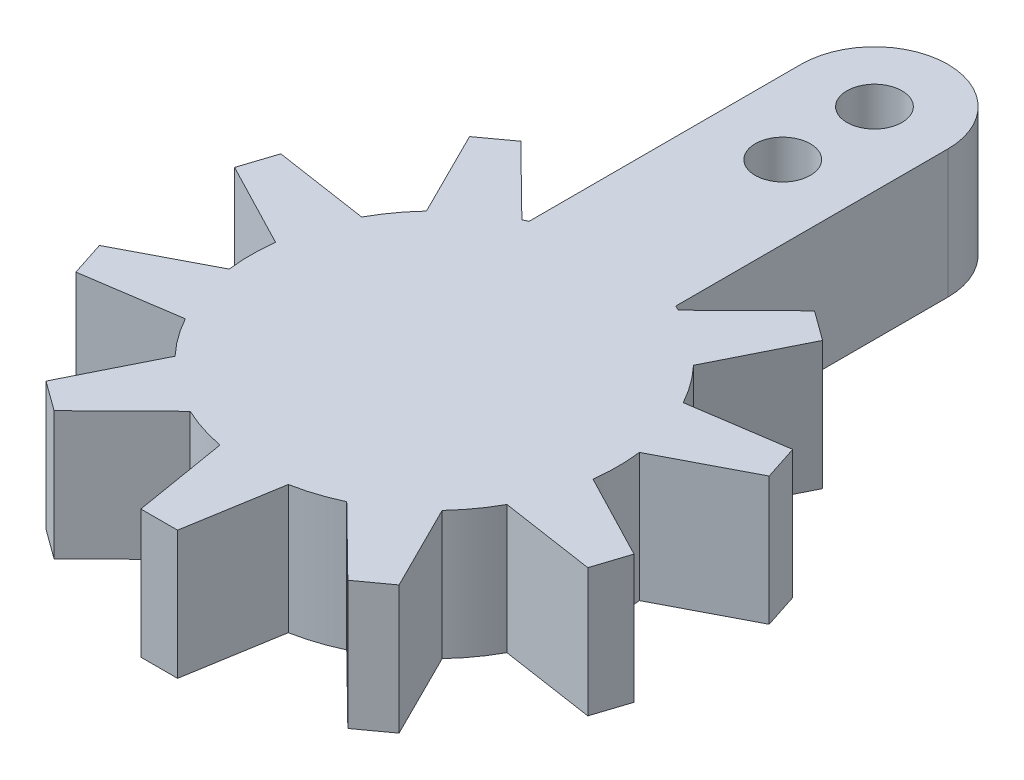
SolidWorks part; units mm, degrees
ref_plane "Front Plane" through (0, 0, 0) normal (0, 0, 1) x (1, 0, 0)
ref_plane "Top Plane" through (0, 0, 0) normal (0, 1, 0) x (1, 0, 0)
ref_plane "Right Plane" through (0, 0, 0) normal (1, 0, 0) x (0, 0, -1)
sketch "Sketch1" plane through (0, 0, 0) normal (0, 1, 0) x (1, 0, 0)
  line L0 (0, 15) -> (0, 10) construction
  line L1 (-1, 15) -> (1, 15)
  line L2 (-1, 15) -> (-2, 9)
  line L3 (1, 15) -> (2, 9)
  line L4 (-2, 9) -> (2, 9)
  line L5 (3.672, 8.4567) -> (6.9081, 6.1056)
  line L6 (9.6258, 11.5475) -> (6.9081, 6.1056)
  line L7 (8.0078, 12.723) -> (9.6258, 11.5475)
  line L8 (8.0078, 12.723) -> (3.672, 8.4567)
  line L9 (7.9415, 4.6833) -> (9.1775, 0.879)
  line L10 (14.5749, 3.6842) -> (9.1775, 0.879)
  line L11 (13.9568, 5.5863) -> (14.5749, 3.6842)
  line L12 (13.9568, 5.5863) -> (7.9415, 4.6833)
  line L13 (9.1775, -0.879) -> (7.9415, -4.6833)
  line L14 (13.9568, -5.5863) -> (7.9415, -4.6833)
  line L15 (14.5749, -3.6842) -> (13.9568, -5.5863)
  line L16 (14.5749, -3.6842) -> (9.1775, -0.879)
  line L17 (6.9081, -6.1056) -> (3.672, -8.4567)
  line L18 (8.0078, -12.723) -> (3.672, -8.4567)
  line L19 (9.6258, -11.5475) -> (8.0078, -12.723)
  line L20 (9.6258, -11.5475) -> (6.9081, -6.1056)
  line L21 (2, -9) -> (-2, -9)
  line L22 (-1, -15) -> (-2, -9)
  line L23 (1, -15) -> (-1, -15)
  line L24 (1, -15) -> (2, -9)
  line L25 (-3.672, -8.4567) -> (-6.9081, -6.1056)
  line L26 (-9.6258, -11.5475) -> (-6.9081, -6.1056)
  line L27 (-8.0078, -12.723) -> (-9.6258, -11.5475)
  line L28 (-8.0078, -12.723) -> (-3.672, -8.4567)
  line L29 (-7.9415, -4.6833) -> (-9.1775, -0.879)
  line L30 (-14.5749, -3.6842) -> (-9.1775, -0.879)
  line L31 (-13.9568, -5.5863) -> (-14.5749, -3.6842)
  line L32 (-13.9568, -5.5863) -> (-7.9415, -4.6833)
  line L33 (-9.1775, 0.879) -> (-7.9415, 4.6833)
  line L34 (-13.9568, 5.5863) -> (-7.9415, 4.6833)
  line L35 (-14.5749, 3.6842) -> (-13.9568, 5.5863)
  line L36 (-14.5749, 3.6842) -> (-9.1775, 0.879)
  line L37 (-6.9081, 6.1056) -> (-3.672, 8.4567)
  line L38 (-8.0078, 12.723) -> (-3.672, 8.4567)
  line L39 (-9.6258, 11.5475) -> (-8.0078, 12.723)
  line L40 (-9.6258, 11.5475) -> (-6.9081, 6.1056)
  line L41 (0, 9) -> (0, 10) construction
  circle A0 centre (0, 0) radius 10
  circle A1 centre (0, 0) radius 15 construction
  point P9 (0, 15)
  point P50 (0, 0)
  dimension "D1" = 5
  dimension "D2" = 20
  dimension "D3" = 2
  dimension "D4" = 4
  dimension "D6" = 1
  dimension "D7" = 1
  dimension "D5" = 10
extrude "Boss-Extrude2" add sketch "Sketch1" along normal blind 7 contours L24 A0 L18 L17 L20 L14 L13 L16 L10 L9 L12 L6 L5 L8 L3 L4 L2 L38 L37 L40 L34 L33 L36 L30 L29 L32 L26 L25 L28 L22 L21 | A0 L30 L31 L32 | A0 L26 L27 L28 | A0 L22 L23 L24 | A0 L18 L19 L20 | A0 L14 L15 L16 | A0 L10 L11 L12 | A0 L6 L7 L8 | A0 L3 L1 L2 | A0 L38 L39 L40 | A0 L34 L35 L36 | L34 A0 L36 L33 | L22 A0 L24 L21 | L18 A0 L20 L17 | L26 A0 L28 L25 | L30 A0 L32 L29 | L38 A0 L40 L37 | L3 A0 L2 L4 | L6 A0 L8 L5 | L10 A0 L12 L9 | L14 A0 L16 L13
sketch "Sketch2" plane through (0, 0, 0) normal (0, -1, 0) x (1, 0, 0)
  line L0 (0, 0) -> (0, -41.646) construction
  line L1 (-4, 0) -> (4, 0)
  line L2 (-4, 0) -> (-4, -24)
  line L4 (4, -24) -> (4, 0)
  arc A0 (-4, -24) -> (4, -24) centre (0, -24) ccw
  circle A1 centre (0, -24) radius 1.5
  circle A2 centre (0, -19) radius 1.5
  point P6 (0, 0)
  dimension "D3" = 4
  dimension "D4" = 3
  dimension "D5" = 19
  dimension "D1" = 8
  dimension "D2" = 24
extrude "Boss-Extrude3" add sketch "Sketch2" against normal blind 7
